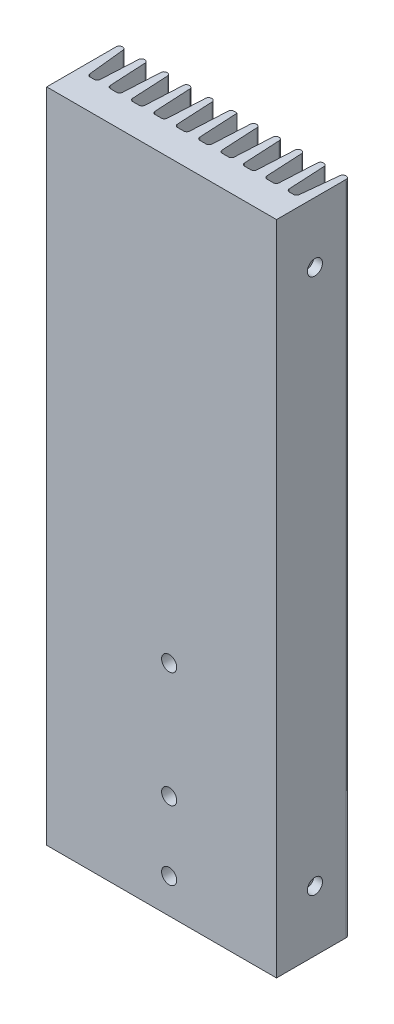
SolidWorks part; units mm, degrees
ref_plane "Front Plane" through (0, 0, 0) normal (0, 0, 1) x (1, 0, 0)
ref_plane "Top Plane" through (0, 0, 0) normal (0, 1, 0) x (1, 0, 0)
ref_plane "Right Plane" through (0, 0, 0) normal (1, 0, 0) x (0, 0, -1)
sketch "Sketch1" plane through (0, 0, 0) normal (0, 1, 0) x (1, 0, 0)
  line L0 (0, 12) -> (0, 0)
  line L1 (0, 0) -> (38, 0)
  line L3 (0, 12) -> (1, 12)
  line L4 (1, 12) -> (1.7357, 5)
  line L26 (1.7357, 5) -> (36.2643, 5)
  line L32 (37, 12) -> (38, 12)
  line L41 (38, 0) -> (38, 12)
  line L42 (36.2643, 5) -> (37, 12)
  dimension "D1" = 38
  dimension "D2" = 12
  dimension "D3" = 6
  dimension "D7" = 6
  dimension "D21" = 1
extrude "Extrude1" add sketch "Sketch1" along normal blind 108.6
sketch "Sketch3" plane through (0, 108.6, 0) normal (0, 1, 0) x (1, 0, 0)
  line L0 (3.3331, 5) -> (3.7, 12)
  line L1 (3.7, 12) -> (4.7, 12)
  line L2 (4.7, 12) -> (5.0669, 5)
  line L3 (3.3331, 5) -> (5.0669, 5)
  line L4 (4.2, 12) -> (4.2, -2.4726) construction
  line L5 (0, 12) -> (0, 0) construction
  dimension "D1" = 4.2
  dimension "D2" = 1
extrude "Boss-Extrude1" add sketch "Sketch3" against normal up to surface (108.6 mm away) up to face at (19, 0, -7.25)
pattern_linear "LPattern1" count 9 spacing 3.7 along (1, 0, 0) of "Boss-Extrude1"
fillet "Fillet1" radius 0.5 20 edges at (36.2643, 54.3, -5) (30.9669, 54.3, -5) (29.2331, 54.3, -5) (27.2669, 54.3, -5) (25.5331, 54.3, -5) (23.5669, 54.3, -5) (21.8331, 54.3, -5) (19.8669, 54.3, -5) (18.1331, 54.3, -5) (16.1669, 54.3, -5) (14.4331, 54.3, -5) (12.4669, 54.3, -5) (10.7331, 54.3, -5) (8.7669, 54.3, -5) (7.0331, 54.3, -5) (1.7357, 54.3, -5) (5.0669, 54.3, -5) (3.3331, 54.3, -5) (34.6669, 54.3, -5) (32.9331, 54.3, -5)
fillet "Fillet2" radius 0.5 21 edges at (38, 54.3, -12) (37, 54.3, -12) (34.3, 54.3, -12) (33.3, 54.3, -12) (30.6, 54.3, -12) (29.6, 54.3, -12) (26.9, 54.3, -12) (25.9, 54.3, -12) (23.2, 54.3, -12) (22.2, 54.3, -12) (18.5, 54.3, -12) (15.8, 54.3, -12) (14.8, 54.3, -12) (12.1, 54.3, -12) (11.1, 54.3, -12) (8.4, 54.3, -12) (7.4, 54.3, -12) (4.7, 54.3, -12) (3.7, 54.3, -12) (1, 54.3, -12) (0, 54.3, -12)
sketch "Sketch5" plane through (38, 0, 0) normal (1, 0, 0) x (0, 0, -1)
  line L0 (0, 108.6) -> (0, 0) construction
  line L1 (5.4477, 108.6) -> (11.5523, 108.6) construction
  line L2 (0, 0) -> (11.5, 0) construction
  circle A0 centre (6.35, 98.6) radius 2.1
  circle A1 centre (6.35, 10) radius 2.1
  point P4 (8.5, 108.6)
  dimension "D1" = 6.35
  dimension "D2" = 10
  dimension "D3" = 4.2
  dimension "D4" = 10
  dimension "D6" = 4.2
  dimension "D5" = 6.35
extrude "Cut-Extrude1" [suppressed] cut sketch "Sketch5" against normal blind 2.5
hole_wizard "M3x0.5 Tapped Hole1" positions "Sketch7" profile "Sketch6" tap size "M3x0.5" standard "Ansi Metric"
sketch "Sketch7" plane through (38, 0, 0) normal (1, 0, 0) x (0, 0, -1)
  line L0 (0, 108.6) -> (0, 0) construction
  line L1 (0, 108.6) -> (11.5, 108.6) construction
  line L2 (0, 0) -> (11.5, 0) construction
  point P0 (6.35, 98.6)
  point P6 (6.35, 10)
  dimension "D1" = 6.35
  dimension "D2" = 10
  dimension "D3" = 6.35
  dimension "D4" = 10
sketch "Sketch6" plane through (38, 98.6, -6.35) normal (0, 1, 0) x (0, 0, -1)
  line L0 (0, 0) -> (0, 7.2511)
  line L1 (0, 7.2511) -> (1.25, 6.5)
  line L2 (1.25, 6.5) -> (1.25, 0)
  line L5 (1.25, 0) -> (0, 0)
  line L10 (0, 7.2511) -> (-1.25, 6.5) construction
  line L11 (0, -6.35) -> (0, 107.95) construction
  dimension "Tap Drill Dia." = 2.5
  dimension "Tap Drill Depth" = 6.5
  dimension "Drill Angle" = 118
cosmetic thread "Hole Thread1" parameters "D1"=5, "D2"=3
cosmetic thread "Hole Thread2" parameters "D1"=5, "D2"=3
hole_wizard "M3x0.5 Tapped Hole2" positions "Sketch9" profile "Sketch8" tap size "M3x0.5" standard "Ansi Metric"
sketch "Sketch9" plane through (0, 0, 0) normal (0, 0, 1) x (1, 0, 0)
  line L0 (38, 108.6) -> (38, 0) construction
  line L1 (0, 108.6) -> (38, 108.6) construction
  point P0 (20.25, 36.21)
  point P1 (20.25, 17.16)
  point P3 (20.25, 5.73)
  dimension "D1" = 17.75
  dimension "D2" = 17.75
  dimension "D3" = 17.75
  dimension "D4" = 72.39
  dimension "D5" = 91.44
  dimension "D6" = 102.87
sketch "Sketch8" plane through (20.25, 36.21, 0) normal (1, 0, 0) x (0, -1, 0)
  line L0 (0, 0) -> (0, 5.7511)
  line L1 (0, 5.7511) -> (1.25, 5)
  line L2 (1.25, 5) -> (1.25, 0)
  line L5 (1.25, 0) -> (0, 0)
  line L10 (0, 5.7511) -> (-1.25, 5) construction
  line L11 (0, -6.35) -> (0, 107.95) construction
  dimension "Tap Drill Dia." = 2.5
  dimension "Tap Drill Depth" = 5
  dimension "Drill Angle" = 118
cosmetic thread "Hole Thread3" parameters "D1"=5, "D2"=3
cosmetic thread "Hole Thread4" parameters "D1"=5, "D2"=3
cosmetic thread "Hole Thread5" parameters "D1"=5, "D2"=3
